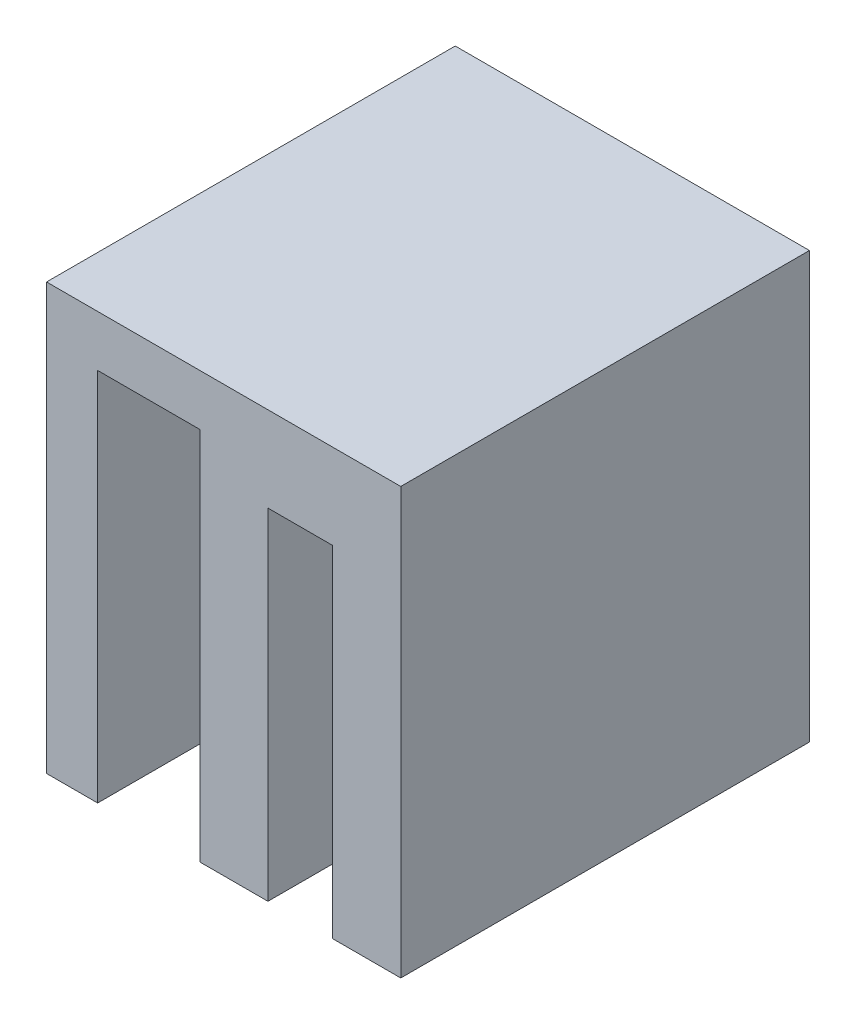
SolidWorks part; units mm, degrees
ref_plane "Front Plane" through (0, 0, 0) normal (0, 0, 1) x (1, 0, 0)
ref_plane "Top Plane" through (0, 0, 0) normal (0, 1, 0) x (1, 0, 0)
ref_plane "Right Plane" through (0, 0, 0) normal (1, 0, 0) x (0, 0, -1)
sketch "Sketch1" plane through (0, 0, 0) normal (0, 0, 1) x (1, 0, 0)
  line L0 (0, 0) -> (45.9503, 0) construction
  line L1 (0, 0) -> (0, -43.168) construction
  line L2 (-1.9, 0) -> (-1.9, -43.168) construction
  line L3 (-1.9, -10) -> (-1.9, 0)
  line L4 (-1.9, 0) -> (0, 0)
  line L5 (0, 0) -> (0, -10)
  line L6 (0, -10) -> (2, -10)
  line L7 (2, -10) -> (2, 2.5)
  line L8 (2, 2.5) -> (-5, 2.5)
  line L9 (-3.9, 1) -> (-3.9, -10)
  line L10 (-3.9, -10) -> (-1.9, -10)
  line L11 (-8, 2.5) -> (-8.4, 2.5)
  line L12 (-5, 2.5) -> (-8, 2.5)
  line L14 (-3.9, 1) -> (-7, 1)
  line L24 (-8.4, 2.5) -> (-8.4, -10)
  line L28 (-6.9, -1) -> (-6.9, 1)
  line L29 (-6.9, 1) -> (-7, 1)
  line L30 (-6.9, -1) -> (-6.9, -10)
  line L31 (-8.4, -10) -> (-6.9, -10)
  dimension "D2" = 2
  dimension "D3" = 2.5
  dimension "D4" = 2
  dimension "D5" = 10
  dimension "D6" = 10
  dimension "D7" = 3
  dimension "D8" = 2
  dimension "D9" = 1.5
  dimension "D12" = 1.5
  dimension "D1" = 1.9
extrude "Boss-Extrude1" add sketch "Sketch1" along normal blind 12
